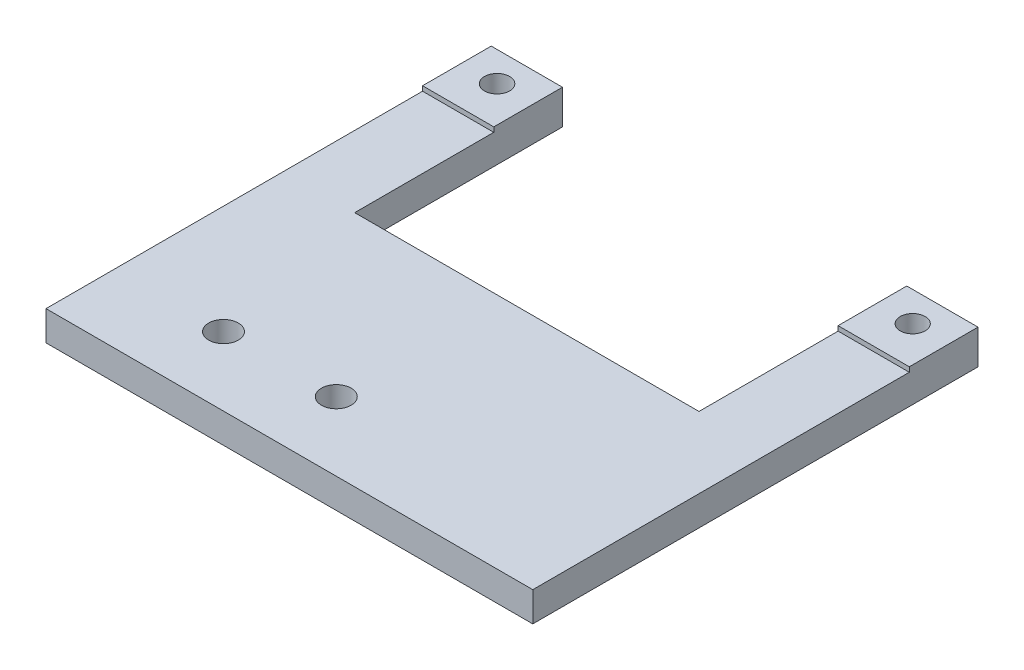
SolidWorks part; units mm, degrees
ref_plane "Front Plane" through (0, 0, 0) normal (0, 0, 1) x (1, 0, 0)
ref_plane "Top Plane" through (0, 0, 0) normal (0, 1, 0) x (1, 0, 0)
ref_plane "Right Plane" through (0, 0, 0) normal (1, 0, 0) x (0, 0, -1)
sketch "Sketch1" plane through (0, 0, 0) normal (0, 1, 0) x (1, 0, 0)
  line L0 (-23.2815, -31.3176) -> (-23.2815, -39.3176) construction
  line L1 (-37.7815, -28.8176) -> (-43.7815, -28.8176)
  line L2 (-40.7815, -31.3176) -> (-5.7815, -31.3176)
  line L3 (-23.2815, -12.1364) -> (-23.2815, -85.4161) construction
  line L4 (-43.7815, -28.8176) -> (-43.7815, -66.3176)
  line L5 (-43.7815, -66.3176) -> (-2.7815, -66.3176)
  line L6 (-23.2815, -66.3176) -> (-23.2815, -46.3176)
  line L7 (-8.7815, -46.3176) -> (-37.7815, -46.3176)
  line L8 (-37.7815, -46.3176) -> (-37.7815, -28.8176)
  line L9 (-2.7815, -28.8176) -> (-2.7815, -66.3176)
  line L10 (-8.7815, -28.8176) -> (-2.7815, -28.8176)
  line L11 (-8.7815, -46.3176) -> (-8.7815, -28.8176)
  circle A0 centre (-23.2815, -31.3176) radius 14
  circle A1 centre (-40.7815, -31.3176) radius 1.05
  circle A2 centre (-5.7815, -31.3176) radius 1.05
  circle A3 centre (-23.2815, -39.3176) radius 1.25
  point P9 (-23.2815, -31.3176)
  dimension "D2" = 28
  dimension "D1" = 2.1
  dimension "D4" = 2.1
  dimension "D6" = 2.5
  dimension "D8" = 15
  dimension "D3" = 35
  dimension "D5" = 8
  dimension "D7" = 17.5
  dimension "D9" = 20
  dimension "D10" = 3
  dimension "D11" = 3
extrude "Boss-Extrude1" add sketch "Sketch1" along normal blind 2.5
sketch "Sketch2" plane through (0, 2.5, 0) normal (0, 1, 0) x (1, 0, 0)
  line L0 (-34.6315, -60.5176) -> (-25.1315, -60.5176) construction
  line L1 (-34.6315, -60.5176) -> (-39.7815, -60.5176) construction
  line L2 (-43.7815, -28.8176) -> (-43.7815, -66.3176) construction
  line L3 (-8.7815, -46.3176) -> (-37.7815, -46.3176) construction
  circle A0 centre (-34.6315, -60.5176) radius 1.25
  circle A1 centre (-25.1315, -60.5176) radius 1.25
  dimension "D2" = 2.5
  dimension "D3" = 2.5
  dimension "D1" = 9.5
  dimension "D4" = 5.15
  dimension "D5" = 4
  dimension "D6" = 14.2
extrude "Cut-Extrude1" cut sketch "Sketch2" along normal through all from surface at -2.5 starting at face at (-23.2815, 0, 42.5676)
sketch "Sketch3" plane through (0, 2.5, 0) normal (0, 1, 0) x (1, 0, 0)
  line L0 (-43.7815, -28.8176) -> (-43.7815, -66.3176) construction
  line L1 (-37.7815, -28.8176) -> (-43.7815, -28.8176)
  line L2 (-37.7815, -28.8176) -> (-37.7815, -34.6026)
  line L3 (-37.7815, -34.6026) -> (-43.7815, -34.6026)
  line L4 (-43.7815, -28.8176) -> (-43.7815, -34.6026)
  line L5 (-23.2815, -66.3176) -> (-23.2815, -21.4375) construction
  line L6 (-43.7815, -66.3176) -> (-2.7815, -66.3176) construction
  line L7 (-8.7815, -34.6026) -> (-2.7815, -34.6026)
  line L8 (-2.7815, -28.8176) -> (-2.7815, -34.6026)
  line L9 (-8.7815, -28.8176) -> (-2.7815, -28.8176)
  line L10 (-8.7815, -28.8176) -> (-8.7815, -34.6026)
extrude "Boss-Extrude2" add sketch "Sketch3" along normal blind 0.4
sketch "Sketch4" plane through (0, 0, 0) normal (0, -1, 0) x (1, 0, 0)
  circle A1 centre (-5.7815, 31.3176) radius 1.05
  circle A2 centre (-40.7913, 31.3176) radius 1.0598
extrude "Cut-Extrude2" cut sketch "Sketch4" against normal through all
